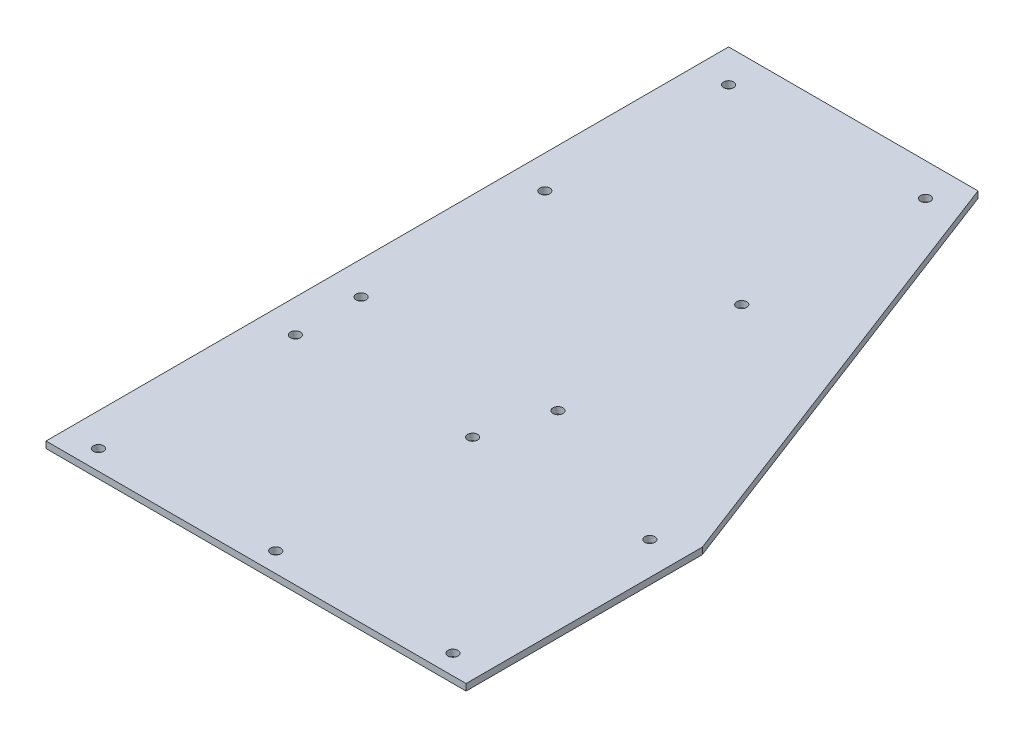
SolidWorks part; units mm, degrees
material "5052-H32"
ref_plane "Front" through (0, 0, 0) normal (0, 0, 1) x (1, 0, 0)
ref_plane "Top" through (0, 0, 0) normal (0, 1, 0) x (1, 0, 0)
ref_plane "Right" through (0, 0, 0) normal (1, 0, 0) x (0, 0, -1)
sketch "Sketch1" plane through (0, 0, 0) normal (0, 1, 0) x (1, 0, 0)
  line L0 (0, 0) -> (203.2, 0)
  line L1 (203.2, 0) -> (203.2, 114.3)
  line L2 (0, 0) -> (0, 330.2)
  line L3 (0, 330.2) -> (120.65, 330.2)
  line L4 (120.65, 330.2) -> (203.2, 114.3)
  line L5 (203.2, 114.3) -> (0, 114.3) construction
  line L6 (120.65, 330.2) -> (120.65, 114.3) construction
  line L7 (15.875, 136.525) -> (15.875, 314.325) construction
  line L8 (111.125, 136.525) -> (111.125, 314.325) construction
  line L9 (15.875, 314.325) -> (111.125, 314.325) construction
  circle A0 centre (15.875, 9.525) radius 2.4257
  circle A1 centre (101.6, 9.525) radius 2.4257
  circle A2 centre (187.325, 9.525) radius 2.4257
  circle A3 centre (15.875, 104.775) radius 2.4257
  circle A5 centre (187.325, 104.775) radius 2.4257
  circle A7 centre (101.6, 104.775) radius 2.4257
  circle A8 centre (15.875, 136.525) radius 2.4257
  circle A9 centre (111.125, 136.525) radius 2.4257
  circle A10 centre (15.875, 225.425) radius 2.4257
  circle A11 centre (15.875, 314.325) radius 2.4257
  circle A12 centre (111.125, 225.425) radius 2.4257
  circle A13 centre (111.125, 314.325) radius 2.4257
  dimension "D5" = 4.8514
  dimension "D1" = 203.2
  dimension "D2" = 114.3
  dimension "D3" = 9.525
  dimension "D4" = 15.875
  dimension "D7" = 85.725
  dimension "D9" = 95.25
  dimension "D10" = 330.2
  dimension "D11" = 22.225
  dimension "D12" = 95.25
  dimension "D13" = 15.875
  dimension "D14" = 120.65
  dimension "D6" = 3
  dimension "D8" = 2
extrude "Boss-Extrude1" add sketch "Sketch1" along normal blind 3.175
fillet "Fillet1" [suppressed] radius 3.175
sketch "Sketch2" plane through (0, 3.175, 0) normal (0, 1, 0) x (1, 0, 0)
  line L0 (15.875, 225.425) -> (111.125, 225.425) construction
  line L1 (15.875, 136.525) -> (111.125, 136.525) construction
  line L6 (63.5, 136.525) -> (63.5, 225.425) construction
  line L8 (28.575, 215.9) -> (98.425, 215.9)
  line L9 (28.575, 215.9) -> (28.575, 146.05)
  line L10 (28.575, 146.05) -> (98.425, 146.05)
  line L11 (98.425, 215.9) -> (98.425, 146.05)
  line L12 (28.575, 215.9) -> (98.425, 146.05) construction
  line L13 (28.575, 146.05) -> (98.425, 215.9) construction
  point P9 (63.5, 180.975)
  dimension "D1" = 69.85
extrude "Cut-Extrude1" [suppressed] cut sketch "Sketch2" against normal through all
fillet "Fillet3" [suppressed] radius 6.35
